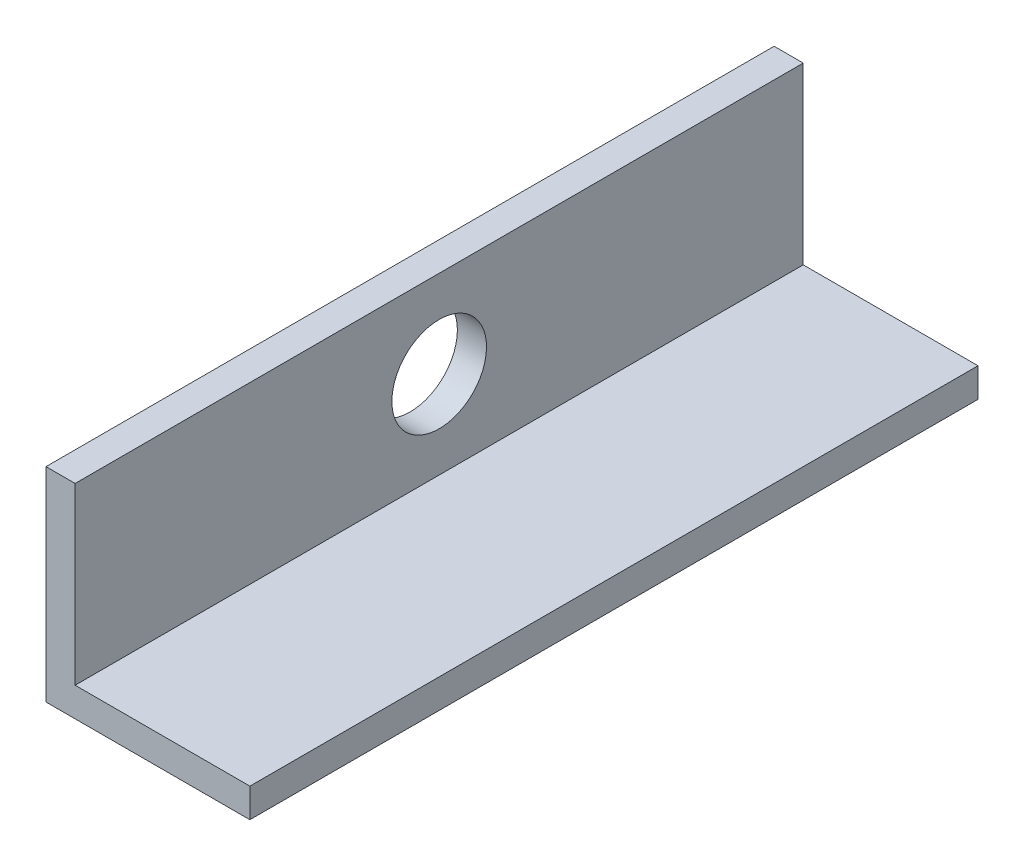
SolidWorks part; units mm, degrees
material "5086-H32, Стержень (SS)"
ref_plane "Спереди" through (0, 0, 0) normal (0, 0, 1) x (1, 0, 0)
ref_plane "Сверху" through (0, 0, 0) normal (0, 1, 0) x (1, 0, 0)
ref_plane "Справа" through (0, 0, 0) normal (1, 0, 0) x (0, 0, -1)
sketch "Эскиз1" plane through (0, 0, 0) normal (0, 0, 1) x (1, 0, 0)
  line L0 (0, 0) -> (0, 14)
  line L1 (0, 14) -> (2, 14)
  line L2 (2, 14) -> (2, 2)
  line L3 (2, 2) -> (14, 2)
  line L4 (14, 2) -> (14, 0)
  line L5 (14, 0) -> (0, 0)
  dimension "D1" = 14
  dimension "D2" = 2
  dimension "D3" = 2
  dimension "D4" = 14
extrude "Бобышка-Вытянуть1" add sketch "Эскиз1" along normal blind 50
sketch "Эскиз2" plane through (2, 0, 0) normal (1, 0, 0) x (0, 0, -1)
  line L0 (-50, 2) -> (-50, 14) construction
  line L1 (-50, 14) -> (0, 14) construction
  circle A0 centre (-25, 8) radius 3.25
  dimension "D1" = 6.5
  dimension "D2" = 25
  dimension "D3" = 6
extrude "Вырез-Вытянуть1" cut sketch "Эскиз2" against normal blind 50
